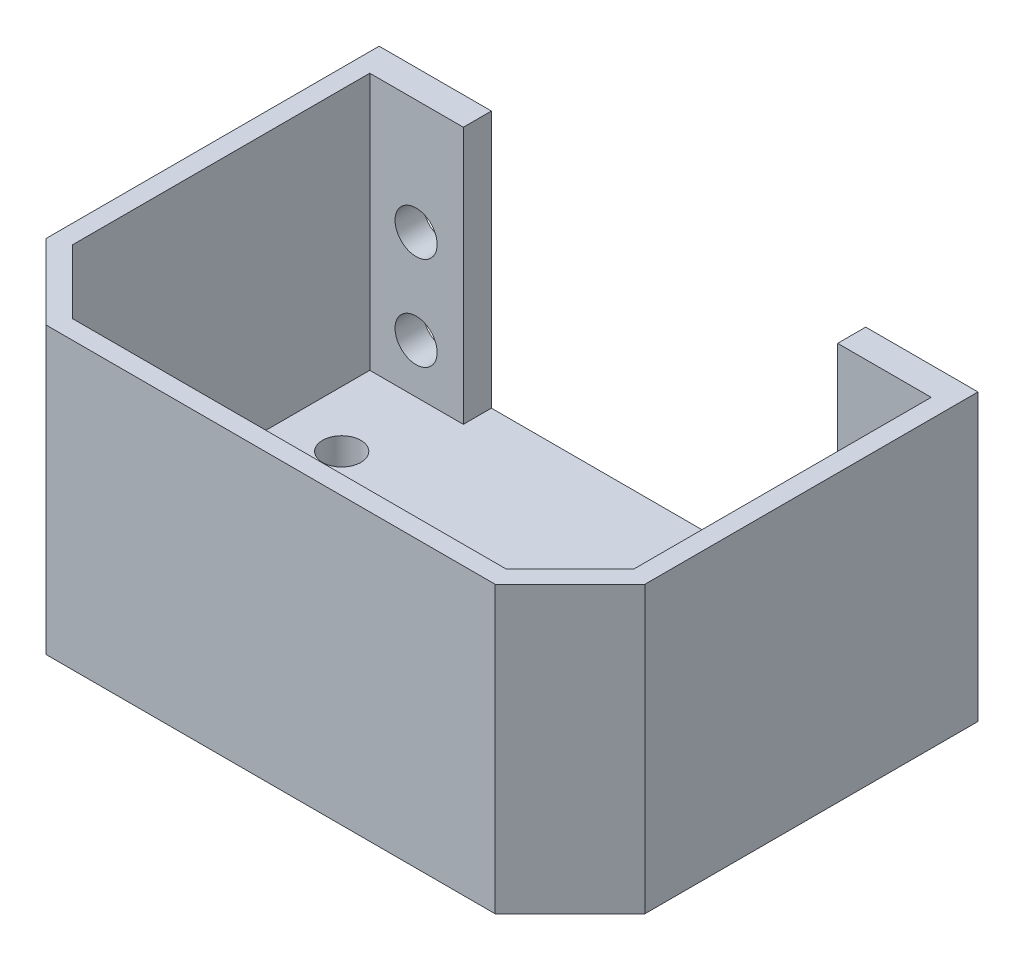
SolidWorks part; units mm, degrees
ref_plane "Front Plane" through (0, 0, 0) normal (0, 0, 1) x (1, 0, 0)
ref_plane "Top Plane" through (0, 0, 0) normal (0, 1, 0) x (1, 0, 0)
ref_plane "Right Plane" through (0, 0, 0) normal (1, 0, 0) x (0, 0, -1)
sketch "Sketch1" plane through (0, 0, 0) normal (0, 0, 1) x (1, 0, 0)
  line L0 (-32, 10.25) -> (-20, 10.25)
  line L5 (32, 10.25) -> (32, -10.25)
  line L6 (32, -10.25) -> (20, -10.25)
  line L7 (-32, -10.25) -> (-32, 10.25)
  line L11 (20, -10.25) -> (-20, -10.25) construction
  line L12 (-20, -10.25) -> (-32, -10.25)
  line L15 (-20, 10.25) -> (-20, -10.25)
  line L16 (20, 10.25) -> (32, 10.25)
  line L17 (20, 10.25) -> (20, -10.25)
  point P6 (-32, 0)
  dimension "D1" = 64
  dimension "D2" = 12
  dimension "D3" = 12
  dimension "D4" = 20.5
  dimension "D5" = 32
  dimension "D6" = 20.5
extrude "Arm Mounts" add sketch "Sketch1" along normal blind 3 contours L16 L17 L6 L5 | L15 L0 L7 L12
sketch "Sketch2" plane through (0, 0, 3) normal (0, 0, -1) x (-1, 0, 0)
  line L0 (0, 55) -> (0, -55) construction
  circle A0 centre (-25.05, 5) radius 2.25
  circle A1 centre (-25.05, -5) radius 2.25
  circle A2 centre (25.05, -5) radius 2.25
  circle A3 centre (25.05, 5) radius 2.25
  dimension "D1" = 4.5
  dimension "D2" = 4.5
  dimension "D3" = 10
  dimension "D4" = 5
  dimension "D5" = 25.05
extrude "Arm Holes" cut sketch "Sketch2" against normal blind 3 and the other way through all contours A3 | A2 | A1 | A0
sketch "Sketch3" plane through (0, 0, 0) normal (0, 0, -1) x (-1, 0, 0)
  line L1 (-32, -10.25) -> (32, -10.25)
  line L2 (-32, -10.25) -> (-32, -13.25)
  line L3 (-32, -13.25) -> (32, -13.25)
  line L4 (32, -10.25) -> (32, -13.25)
  line L5 (-32, 10.25) -> (-32, -10.25) construction
  line L6 (32, -10.25) -> (32, 10.25) construction
  line L7 (-32, -10.25) -> (-20, -10.25) construction
  dimension "D1" = 3
extrude "Bottom Plate" add sketch "Sketch3" against normal blind 28
sketch "Sketch4" plane through (-32, 0, 0) normal (-1, 0, 0) x (0, 0, 1)
  line L0 (3, 10.25) -> (28, -10.25)
  line L1 (28, -10.25) -> (3, -10.25)
  line L2 (3, -10.25) -> (3, 10.25)
extrude "Side Ribs" add sketch "Sketch4" against normal blind 2
mirror "Rib Mirror" about plane through (0, 0, 0) normal (1, 0, 0) of "Side Ribs"
sketch "Sketch5" plane through (0, -10.25, 0) normal (0, 1, 0) x (1, 0, 0)
  line L0 (-30, -28) -> (30, -28) construction
  line L1 (28, -28) -> (-8, -28)
  line L2 (28, -28) -> (28, -16)
  line L3 (28, -16) -> (-8, -16)
  line L4 (-8, -28) -> (-8, -16)
  line L5 (32, -28) -> (32, -3) construction
  dimension "D1" = 4
  dimension "D2" = 36
  dimension "D3" = 12
extrude "Cut-Extrude2" cut sketch "Sketch5" against normal blind 10
sketch "Sketch6" plane through (0, -10.25, 0) normal (0, 1, 0) x (1, 0, 0)
  line L0 (-20, 0) -> (20, 0) construction
  circle A0 centre (-24, -12) radius 2.05
  circle A1 centre (24, -10) radius 2.05
  dimension "D5" = 4.1
  dimension "D6" = 4.1
  dimension "D1" = 10
  dimension "D2" = 24
  dimension "D3" = 24
  dimension "D4" = 12
extrude "Mounting Holes" cut sketch "Sketch6" against normal blind 10
sketch "Sketch7" plane through (0, -10.25, 0) normal (0, 1, 0) x (1, 0, 0)
  line L0 (-1002.3277, -21.8) -> (48997.6723, -21.8) construction
  line L1 (-20, 0) -> (20, 0) construction
  dimension "D1" = 21.8
sketch "Sketch8" plane through (0, -10.25, 0) normal (0, 1, 0) x (1, 0, 0)
  line L0 (-201002.3277, -21.8) -> (248997.6723, -21.8) construction
  line L1 (-32, -28) -> (32, -28)
  line L2 (-32, -28) -> (-32, -21.8)
  line L3 (-32, -21.8) -> (32, -21.8)
  line L4 (32, -28) -> (32, -21.8)
  line L5 (32, -28) -> (32, -3) construction
extrude "Cut-Extrude4" cut sketch "Sketch8" against normal through all both and the other way through all
ref_plane "Plane3" through (0, 0, 21.8) normal (0, 0, 1) x (1, 0, 0)
sketch "Sketch10" plane through (0, -10.25, 0) normal (0, 1, 0) x (1, 0, 0)
  line L0 (32, -21.8) -> (32, -3) construction
  line L1 (-32, -21.8) -> (32, -21.8)
  line L2 (-32, -21.8) -> (-32, -43.6)
  line L3 (-32, -43.6) -> (32, -43.6)
  line L4 (32, -21.8) -> (32, -43.6)
  dimension "D1" = 21.8
extrude "Boss-Extrude7" add sketch "Sketch10" against normal up to surface (3 mm away) up to face at (5, -13.25, 14.9)
mirror "Mirror5" about plane through (0, 0, 21.8) normal (0, 0, 1) of "Cut-Extrude2", "Mounting Holes"
chamfer "Chamfer3" distance 5 angle 45 2 edges at (31, -10.25, 21.8) (-31, -10.25, 21.8)
chamfer "Chamfer4" distance 2.5 angle 45 4 edges at (28, -11.75, 27.6) (-8, -11.75, 27.6) (28, -11.75, 15.6) (-8, -11.75, 15.6)
chamfer "Chamfer5" distance 8 angle 45 2 edges at (-32, -11.75, 43.6) (32, -11.75, 43.6)
sketch "Sketch11" plane through (0, -10.25, 0) normal (0, 1, 0) x (1, 0, 0)
  line L3 (-8, -25.1) -> (-8, -26.5142)
  line L4 (-8, -26.5142) -> (-8.7071, -25.8071) construction
  line L5 (28, -25.1) -> (28, -26.5142)
  line L6 (28.7071, -25.8071) -> (25.9142, -28.6)
  line L7 (25.9142, -28.6) -> (-5.9142, -28.6)
  line L8 (-5.9142, -28.6) -> (-8.7071, -25.8071)
  line L9 (28, -26.5142) -> (25.9142, -28.6)
  line L10 (25.9142, -28.6) -> (-5.9142, -28.6)
  line L11 (-5.9142, -28.6) -> (-8, -26.5142)
  line L12 (28.7071, -25.8071) -> (28, -26.5142) construction
  line L13 (-8, -25.1) -> (28, -25.1)
  dimension "D1" = 1
extrude "Cut-Extrude5" cut sketch "Sketch11" against normal blind 10
sketch "Sketch12" plane through (0, -10.25, 0) normal (0, 1, 0) x (1, 0, 0)
  line L0 (-32, -26.8) -> (-32, -3)
  line L1 (-32, -3) -> (-30, -3)
  line L2 (-30, -26.8) -> (-30, -34.7716)
  line L3 (-30, -34.7716) -> (-23.1716, -41.6)
  line L4 (-23.1716, -41.6) -> (23.1716, -41.6)
  line L5 (23.1716, -41.6) -> (30, -34.7716)
  line L6 (30, -34.7716) -> (30, -26.8)
  line L7 (-30, -3) -> (-30, -26.8)
  line L8 (30, -26.8) -> (30, -3)
  line L9 (30, -3) -> (32, -3)
  line L10 (32, -3) -> (32, -26.8)
  line L14 (-32, -26.8) -> (-32, -35.6)
  line L15 (-32, -35.6) -> (-24, -43.6)
  line L16 (-24, -43.6) -> (24, -43.6)
  line L17 (24, -43.6) -> (32, -35.6)
  line L18 (32, -35.6) -> (32, -26.8)
  line L19 (32, -26.8) -> (30, -26.8)
  line L20 (30, -26.8) -> (30, -3)
  line L21 (30, -3) -> (20, -3)
  line L22 (20, -3) -> (20, 0)
  line L23 (20, 0) -> (-20, 0)
  line L24 (-20, 0) -> (-20, -3)
  line L25 (-20, -3) -> (-30, -3)
  line L26 (-30, -3) -> (-30, -26.8)
  line L27 (-30, -26.8) -> (-32, -26.8)
  line L28 (-32, -26.8) -> (-32, -35.6)
  line L29 (-32, -35.6) -> (-24, -43.6)
  line L30 (-24, -43.6) -> (24, -43.6)
  line L31 (24, -43.6) -> (32, -35.6)
  line L32 (32, -35.6) -> (32, -26.8)
  dimension "D1" = 0
  dimension "D2" = 2
extrude "Boss-Extrude8" add sketch "Sketch12" along normal up to surface (20.5 mm away) up to face at (-26.8, 10.25, 1.8)
sketch "Sketch13" plane through (0, 10.25, 0) normal (0, 1, 0) x (1, 0, 0)
  line L16 (-20, 0) -> (-32, 0)
  line L17 (-32, 0) -> (-32, -35.6)
  line L18 (-32, -35.6) -> (-24, -43.6)
  line L19 (-24, -43.6) -> (24, -43.6)
  line L20 (24, -43.6) -> (32, -35.6)
  line L21 (32, -35.6) -> (32, 0)
  line L22 (32, 0) -> (20, 0)
  line L23 (20, 0) -> (20, -3)
  line L24 (20, -3) -> (30, -3)
  line L25 (30, -3) -> (30, -34.7716)
  line L26 (30, -34.7716) -> (23.1716, -41.6)
  line L27 (23.1716, -41.6) -> (-23.1716, -41.6)
  line L28 (-23.1716, -41.6) -> (-30, -34.7716)
  line L29 (-30, -34.7716) -> (-30, -3)
  line L30 (-30, -3) -> (-20, -3)
  line L31 (-20, -3) -> (-20, 0)
  line L32 (-20, 0) -> (-32, 0)
  line L33 (-32, 0) -> (-32, -35.6)
  line L34 (-32, -35.6) -> (-24, -43.6)
  line L35 (-24, -43.6) -> (24, -43.6)
  line L36 (24, -43.6) -> (32, -35.6)
  line L37 (32, -35.6) -> (32, 0)
  line L38 (32, 0) -> (20, 0)
  line L39 (20, 0) -> (20, -3)
  line L40 (20, -3) -> (30, -3)
  line L41 (30, -3) -> (30, -34.7716)
  line L42 (30, -34.7716) -> (23.1716, -41.6)
  line L43 (23.1716, -41.6) -> (-23.1716, -41.6)
  line L44 (-23.1716, -41.6) -> (-30, -34.7716)
  line L45 (-30, -34.7716) -> (-30, -3)
  line L46 (-30, -3) -> (-20, -3)
  line L47 (-20, -3) -> (-20, 0)
  dimension "D1" = 0
extrude "Boss-Extrude9" add sketch "Sketch13" along normal blind 7
